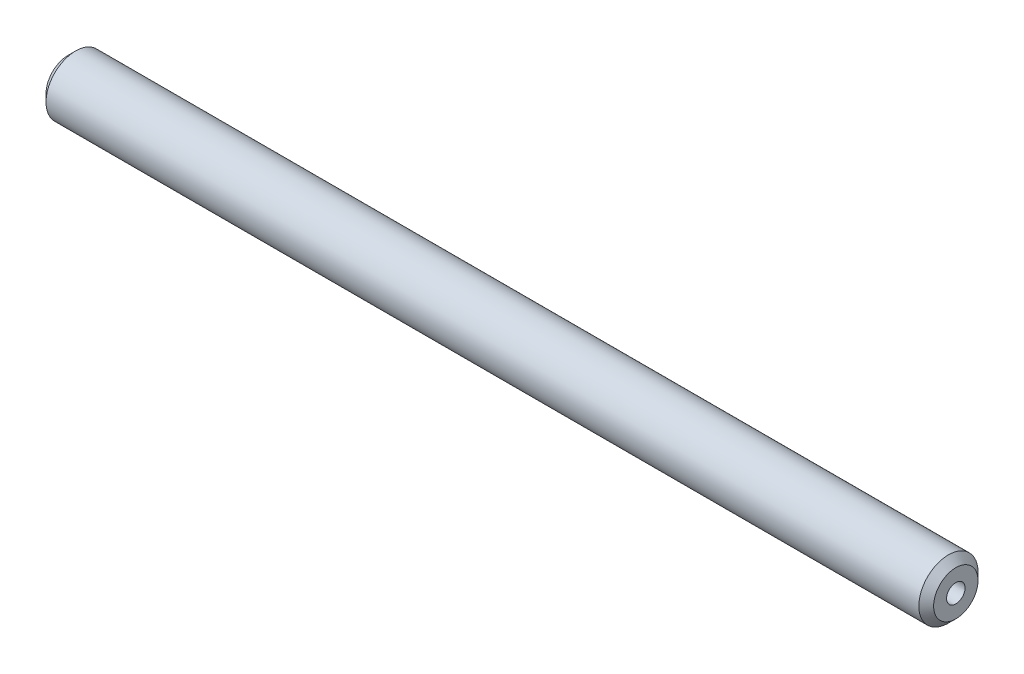
SolidWorks part; units mm, degrees
material "Acier allié inoxydable"
ref_plane "Plan de face" through (0, 0, 0) normal (0, 0, 1) x (1, 0, 0)
ref_plane "Plan de dessus" through (0, 0, 0) normal (0, 1, 0) x (1, 0, 0)
ref_plane "Plan de droite" through (0, 0, 0) normal (1, 0, 0) x (0, 0, -1)
sketch "Esquisse1" plane through (0, 0, 0) normal (1, 0, 0) x (0, 0, -1)
  circle A0 centre (0, 0) radius 4
  dimension "D1" = 8
extrude "Boss.-Extru.1" add sketch "Esquisse1" along normal mid plane 120
chamfer "Chanfrein1" distance 1 angle 45 2 edges at (60, 0, -4) (-60, 0, -4)
hole_wizard "Trou taraudé M31" positions "Esquisse3" profile "Esquisse2" tap size "M3" standard "ISO"
sketch "Esquisse3" plane through (60, 0, 0) normal (1, 0, 0) x (0, 0, -1)
  point P0 (0, 0)
sketch "Esquisse2" plane through (60, 0, 0) normal (0, 1, 0) x (0, 0, -1)
  line L0 (0, 0) -> (0, 9.2511)
  line L1 (0, 9.2511) -> (1.25, 8.5)
  line L2 (1.25, 8.5) -> (1.25, 0)
  line L5 (1.25, 0) -> (0, 0)
  line L10 (0, 9.2511) -> (-1.25, 8.5) construction
  line L11 (0, -6.35) -> (0, 107.95) construction
  dimension "Diamètre du trou pour taraudage" = 2.5
  dimension "Profondeur du trou pour taraudage" = 8.5
  dimension "Angle de pointe" = 118
cosmetic thread "Filetage de perçage1"
hole_wizard "Trou taraudé M32" positions "Esquisse5" profile "Esquisse4" tap size "M3" standard "ISO"
sketch "Esquisse5" plane through (-60, 0, 0) normal (-1, 0, 0) x (0, 0, 1)
  point P0 (0, 0)
sketch "Esquisse4" plane through (-60, 0, 0) normal (0, 1, 0) x (0, 0, 1)
  line L0 (0, 0) -> (0, 9.2511)
  line L1 (0, 9.2511) -> (1.25, 8.5)
  line L2 (1.25, 8.5) -> (1.25, 0)
  line L5 (1.25, 0) -> (0, 0)
  line L10 (0, 9.2511) -> (-1.25, 8.5) construction
  line L11 (0, -6.35) -> (0, 107.95) construction
  dimension "Diamètre du trou pour taraudage" = 2.5
  dimension "Profondeur du trou pour taraudage" = 8.5
  dimension "Angle de pointe" = 118
cosmetic thread "Filetage de perçage2"
